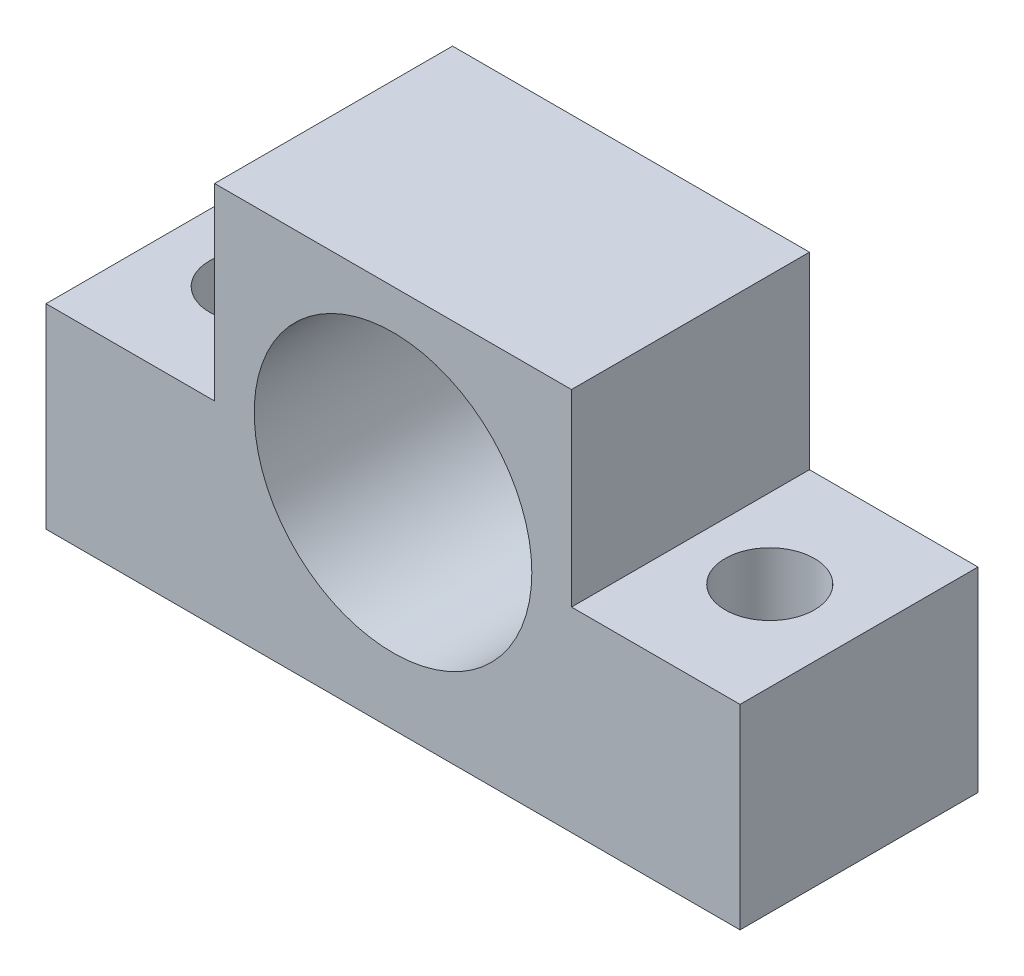
SolidWorks part; units mm, degrees
material "AISI 1045 Aço, trefilado"
ref_plane "Plano frontal" through (0, 0, 0) normal (0, 0, 1) x (1, 0, 0)
ref_plane "Plano superior" through (0, 0, 0) normal (0, 1, 0) x (1, 0, 0)
ref_plane "Plano direito" through (0, 0, 0) normal (1, 0, 0) x (0, 0, -1)
sketch "Esboço1" plane through (0, 0, 0) normal (0, 0, 1) x (1, 0, 0)
  line L0 (-35, 0) -> (35, 0)
  line L1 (35, 0) -> (35, 19.7)
  line L2 (35, 19.7) -> (18, 19.7)
  line L3 (18, 19.7) -> (18, 38.7)
  line L4 (18, 38.7) -> (-18, 38.7)
  line L5 (-18, 38.7) -> (-18, 19.7)
  line L6 (-18, 19.7) -> (-35, 19.7)
  line L7 (-35, 19.7) -> (-35, 0)
  line L8 (0, 20.7) -> (37.5306, 58.2306) construction
  circle A6 centre (0, 20.7) radius 14
  point P4 (0, 0)
  point P12 (0, 38.7)
  dimension "D10" = 28
  dimension "D1" = 19.7
  dimension "D2" = 38.7
  dimension "D3" = 36
  dimension "D4" = 70
  dimension "D7" = 20.7
  dimension "D8" = 45
extrude "Ressalto-extrusão3" add sketch "Esboço1" along normal blind 24
sketch "Sketch2" plane through (0, 19.7, 0) normal (0, 1, 0) x (1, 0, 0)
  line L2 (-18, -24) -> (-35, -24) construction
  line L3 (0, 0) -> (0, -24) construction
  line L4 (18, 0) -> (-18, 0) construction
  line L5 (18, -24) -> (-18, -24) construction
  circle A0 centre (-26, -12) radius 4.5
  circle A1 centre (26, -12) radius 4.5
  dimension "D1" = 9
  dimension "D2" = 12
  dimension "D3" = 52
extrude "Cut-Extrude1" cut sketch "Sketch2" against normal through all
